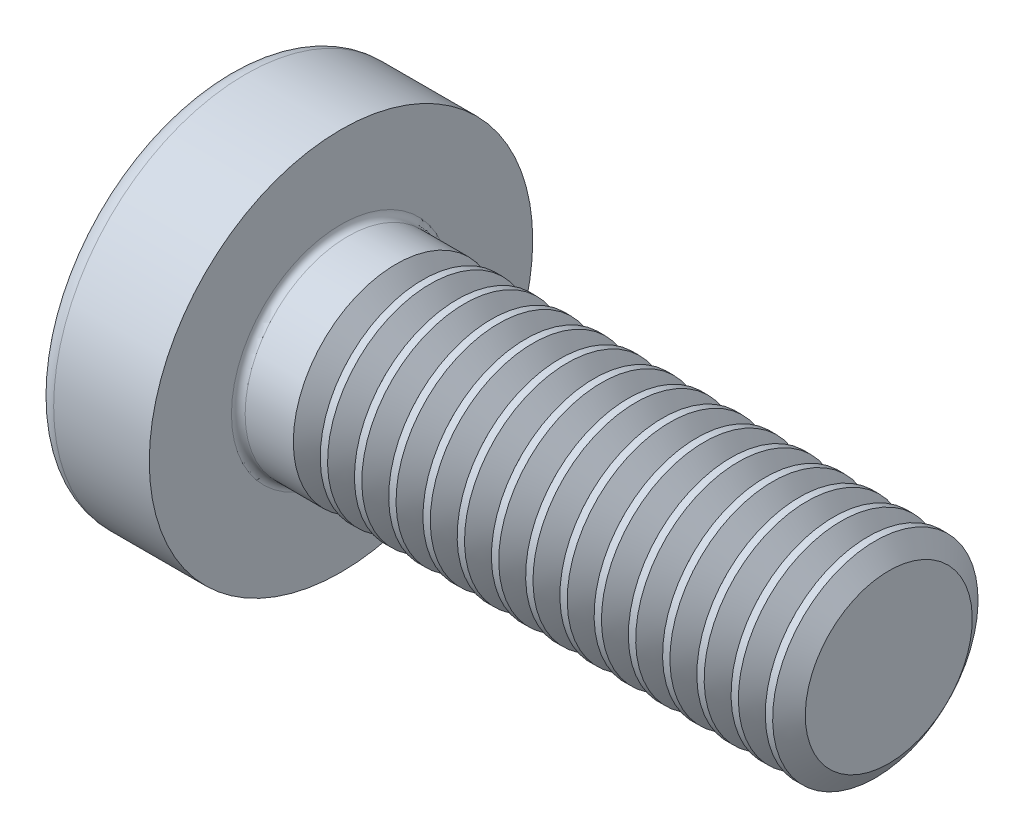
SolidWorks part; units mm, degrees
ref_plane "Plane1" through (0, 0, 0) normal (0, 0, 1) x (1, 0, 0)
ref_plane "Plane2" through (0, 0, 0) normal (0, 1, 0) x (1, 0, 0)
ref_plane "Plane3" through (0, 0, 0) normal (1, 0, 0) x (0, 0, -1)
sketch "BodySke" plane through (0, 0, 0) normal (0, 0, 1) x (1, 0, 0)
  line L0 (2.4, 1.5) -> (2.4, 2.8)
  line L1 (2.65, 6.35) -> (2.65, -3.175) construction
  line L2 (-25.4, 0) -> (127, 0) construction
  line L3 (10.4, 0) -> (0, 0)
  line L4 (2.4, 1.5) -> (10.4, 1.5)
  line L5 (10.4, 1.5) -> (10.4, 0)
  line L6 (1.0035, 2.8) -> (2.4, 2.8)
  line L8 (2.4, 6.35) -> (2.4, -3.175) construction
  arc A0 (0.7754, 2.6744) -> (0, 0) centre (5, 0) ccw
  arc A2 (0.7754, 2.6744) -> (1.0035, 2.8) centre (1.0035, 2.53) cw
  dimension "Head_crown_rad" = 5
  dimension "Head_fillet_rad" = 0.27
  dimension "Length" = 8
  dimension "Head_ht" = 2.4
  dimension "Head_dia" = 5.6
  dimension "Advance" = 0.5
  dimension "Thread_nom" = 8
  dimension "Diameter" = 3
revolve "Base-Revolve" add sketch "BodySke"
cosmetic thread "ThreadCosmetic" [suppressed]
fillet "Fillet1" radius 0.1 1 edges at (2.4, 0, 1.5)
sketch "Sketch3" plane through (0, 0, 0) normal (1, 0, 0) x (0, 0, -1)
  line L0 (0.37, -1.4) -> (-0.37, -1.4)
  line L1 (0.37, -1.4) -> (0.37, 1.4)
  line L2 (-0.37, 1.4) -> (0.37, 1.4)
  line L3 (-0.37, 1.4) -> (-0.37, -1.4)
  dimension "Cross_dia" = 2.8
  dimension "D1" = 1.4
  dimension "Cross_width" = 0.74
  dimension "D2" = 0.37
ref_plane "Plane4" through (1.75, 0, 0) normal (1, 0, 0) x (0, 0, -1)
sketch "Sketch4" plane through (1.75, 0, 0) normal (1, 0, 0) x (0, 0, -1)
  line L0 (0.37, -0.5275) -> (-0.37, -0.5275)
  line L1 (0.37, -0.5275) -> (0.37, 0.5275)
  line L2 (-0.37, 0.5275) -> (0.37, 0.5275)
  line L3 (-0.37, 0.5275) -> (-0.37, -0.5275)
  dimension "D1" = 0.74
  dimension "D2" = 1.055
  dimension "D3" = 0.37
  dimension "D4" = 0.5275
loft "Recess" cut profiles "Sketch3", "Sketch4"
pattern_circular "RecPat" count 2 every 90 about axis through (0, 0, 0) along (1, 0, 0) of "Recess"
sketch "RecCorSke" plane through (0, 0, 0) normal (0, 0, 1) x (1, 0, 0)
  line L0 (-3.175, 0) -> (15.875, 0) construction
  line L1 (-25.4, 0) -> (127, 0) construction
  line L2 (0, 0) -> (0, 0.6784)
  line L3 (0, 0.6784) -> (1.75, 0.556)
  line L4 (1.75, 0.556) -> (1.9307, 0)
  line L5 (1.9307, 0) -> (0, 0)
  dimension "Diameter" = 1.112
  dimension "Depth" = 1.75
  dimension "Draft_angle" = 4
  dimension "Bottom_angle" = 18
revolve "RecessCore" cut sketch "RecCorSke" angle 360 about L0
sketch "ThdSchSke" plane through (0, 0, 0) normal (0, 0, 1) x (1, 0, 0)
  line L0 (3.4, -1.2195) -> (3.2036, -1.5)
  line L1 (3.4, -1.2195) -> (3.5964, -1.5)
  line L2 (3.5964, -1.5) -> (3.5964, -1.875)
  line L3 (-3.175, 0) -> (5.1513, 0) construction
  line L5 (3.5964, -1.875) -> (3.2036, -1.875)
  line L6 (3.2036, -1.875) -> (3.2036, -1.5)
  dimension "Diameter" = 3
  dimension "SideAngle" = 55
  dimension "VeeAngle" = 70
  dimension "Thread_minor" = 2.439
  dimension "Overcut" = 3.75
  dimension "Start" = 3.4
revolve "ThreadSchematic" cut sketch "ThdSchSke" angle 360 about L3
pattern_linear "ThdSchPat" count 15 spacing 0.5 along (1, 0, 0) of "ThreadSchematic"
equation "\"D1@Sketch3\" = \"Cross_dia@Sketch3\" / 2"
equation "\"D2@Sketch3\" = \"Cross_width@Sketch3\" / 2"
equation "\"Depth@RecCorSke\" = \"Cross_depth@Plane4\""
equation "\"D1@Sketch4\" = \"Cross_width@Sketch3\""
equation "\"D2@Sketch4\" = \"Cross_dia@Sketch3\" - 2.0 * \"Cross_depth@Plane4\" * tan(26.5  * 0.017453292)"
equation "\"D3@Sketch4\" = \"D1@Sketch4\" / 2"
equation "\"D4@Sketch4\" = \"D2@Sketch4\" / 2"
equation "\"Thread_length@ThreadCosmetic\" = ((sgn( (\"Length@BodySke\" - \"Advance@BodySke\" * 2.0 ) - \"Thread_nom@BodySke\" )-1)*( (\"Length@BodySke\" - \"Advance@BodySke\" * 2.0 ) - \"Thread_nom@BodySke\" ))/-2+ \"Thread_nom@BodySke\""
equation "\"Thread_minor@ThdSchSke\" = \"Thread_minor@ThreadCosmetic\""
equation "\"Diameter@ThdSchSke\" = \"Diameter@BodySke\""
equation "\"Overcut@ThdSchSke\" = \"Diameter@BodySke\" * 1.25"
equation "\"Start@ThdSchSke\" = \"Head_ht@BodySke\" + \"Length@BodySke\" - \"Thread_length@ThreadCosmetic\"  '---Non-countersunk---"
equation "\"Num_threads@ThdSchPat\" = int( \"Thread_length@ThreadCosmetic\" / \"Advance@BodySke\" + 0.999 )  + 1"
equation "\"Advance@ThdSchPat\" = \"Thread_length@ThreadCosmetic\" /  (\"Num_threads@ThdSchPat\" - 1) 'relax it"
